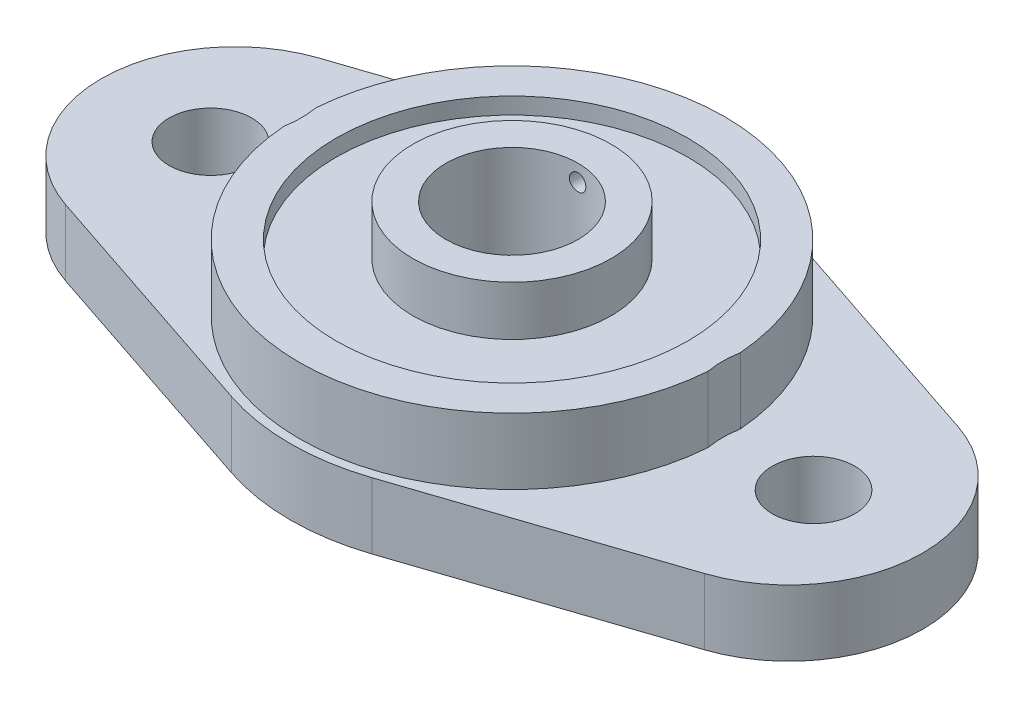
SolidWorks part; units mm, degrees
ref_plane "Front Plane" through (0, 0, 0) normal (0, 0, 1) x (1, 0, 0)
ref_plane "Top Plane" through (0, 0, 0) normal (0, 1, 0) x (1, 0, 0)
ref_plane "Right Plane" through (0, 0, 0) normal (1, 0, 0) x (0, 0, -1)
sketch "Sketch1" plane through (0, 0, 0) normal (0, 1, 0) x (1, 0, 0)
  line L0 (-4.2486, 12.7192) -> (-19.3263, 7.6827)
  line L1 (-19.3263, -7.6827) -> (-4.2486, -12.7192)
  line L2 (4.2486, -12.7192) -> (19.3263, -7.6827)
  line L3 (19.3263, 7.6827) -> (4.2486, 12.7192)
  circle A0 centre (0, 0) radius 10.64
  arc A1 (4.2486, 12.7192) -> (-4.2486, 12.7192) centre (0, 0) ccw
  arc A2 (19.3263, -7.6827) -> (19.3263, 7.6827) centre (16.76, 0) ccw
  arc A3 (-19.3263, 7.6827) -> (-19.3263, -7.6827) centre (-16.76, 0) ccw
  arc A4 (-4.2486, -12.7192) -> (4.2486, -12.7192) centre (0, 0) ccw
  point P11 (42.3261, 0)
  point P14 (-42.3261, 0)
  point P15 (24.86, 0)
  point P20 (0, 13.41)
  dimension "D1" = 21.28
  dimension "D2" = 8.1
  dimension "D4" = 26.82
  dimension "D3" = 24.86
extrude "Boss-Extrude1" add sketch "Sketch1" along normal blind 4
sketch "Sketch2" plane through (0, 4, 0) normal (0, 1, 0) x (1, 0, 0)
  circle A0 centre (0, 0) radius 12.875
  circle A1 centre (0, 0) radius 10.64
  circle A2 centre (0, 0) radius 10.64 construction
  dimension "D2" = 25.75
extrude "Boss-Extrude2" add sketch "Sketch2" along normal blind 4
sketch "Sketch3" plane through (0, 0, 0) normal (0, 1, 0) x (1, 0, 0)
  circle A0 centre (0, 0) radius 4
  circle A1 centre (0, 0) radius 6
  dimension "D1" = 8
  dimension "D2" = 12
extrude "Boss-Extrude3" add sketch "Sketch3" along normal blind 10 separate body
sketch "Sketch5" plane through (0, 0, 0) normal (0, 1, 0) x (1, 0, 0)
  line L0 (-18.25, 0) -> (18.25, 0) construction
  circle A0 centre (-18.25, 0) radius 2.5
  circle A1 centre (18.25, 0) radius 2.5
  point P4 (0, 0)
  dimension "D2" = 5
  dimension "D1" = 36.5
extrude "Cut-Extrude1" cut sketch "Sketch5" along normal up to next (4 mm away)
sketch "Sketch6" plane through (0, 0, 0) normal (0, 1, 0) x (1, 0, 0)
  circle A0 centre (0, 0) radius 6
  circle A1 centre (0, 0) radius 10.64
  circle A2 centre (0, 0) radius 6 construction
  circle A3 centre (0, 0) radius 10.64 construction
extrude "Boss-Extrude4" add sketch "Sketch6" along normal blind 7
sketch "Sketch7" plane through (0, 8, 0) normal (0, 1, 0) x (1, 0, 0)
  circle A0 centre (-18.25, 0) radius 5.5
  circle A1 centre (18.25, 0) radius 5.5
  dimension "D1" = 11
extrude "Cut-Extrude2" cut sketch "Sketch7" against normal up to surface (4 mm away) up to face at (-18.25, 4, 2.5)
sketch "Sketch8" plane through (0, 0, 0) normal (0, 0, 1) x (1, 0, 0)
  line L0 (4, 10) -> (-4, 10) construction
  circle A0 centre (0, 9) radius 0.5
  dimension "D1" = 1
  dimension "D2" = 1
extrude "Cut-Extrude3" cut sketch "Sketch8" against normal through all
